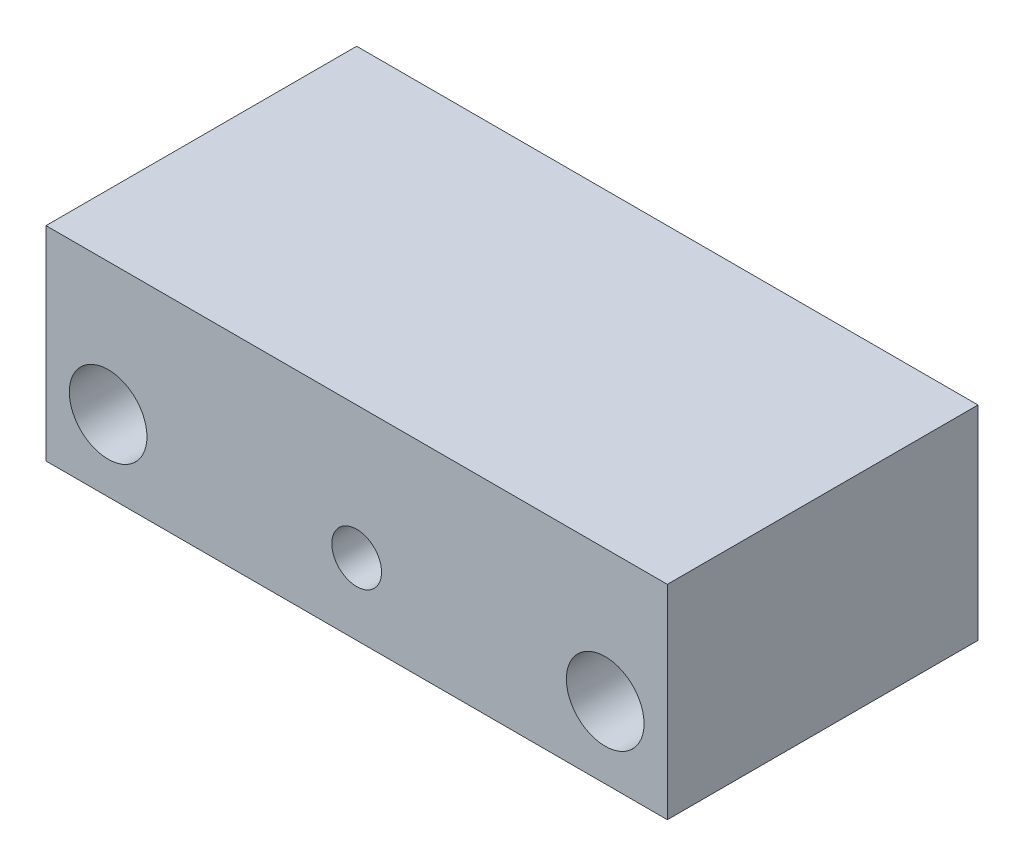
SolidWorks part; units mm, degrees
ref_plane "前视基准面" through (0, 0, 0) normal (0, 0, 1) x (1, 0, 0)
ref_plane "上视基准面" through (0, 0, 0) normal (0, 1, 0) x (1, 0, 0)
ref_plane "右视基准面" through (0, 0, 0) normal (1, 0, 0) x (0, 0, -1)
sketch "草图1" plane through (0, 0, 0) normal (0, 0, 1) x (1, 0, 0)
  line L1 (0, 0) -> (200, 0)
  line L2 (0, 0) -> (0, 65.63)
  line L3 (0, 65.63) -> (200, 65.63)
  line L4 (200, 0) -> (200, 65.63)
  circle A0 centre (20, 23) radius 12.5
  circle A1 centre (100, 23) radius 8
  circle A2 centre (180, 23) radius 12.5
  dimension "D3" = 25
  dimension "D4" = 16
  dimension "D5" = 25
  dimension "D6" = 80
  dimension "D7" = 80
  dimension "D8" = 20
  dimension "D9" = 23
  dimension "D10" = 23
  dimension "D11" = 23
  dimension "D1" = 200
  dimension "D2" = 65.63
extrude "凸台-拉伸1" add sketch "草图1" along normal blind 100
cosmetic thread "装饰螺纹线1"
